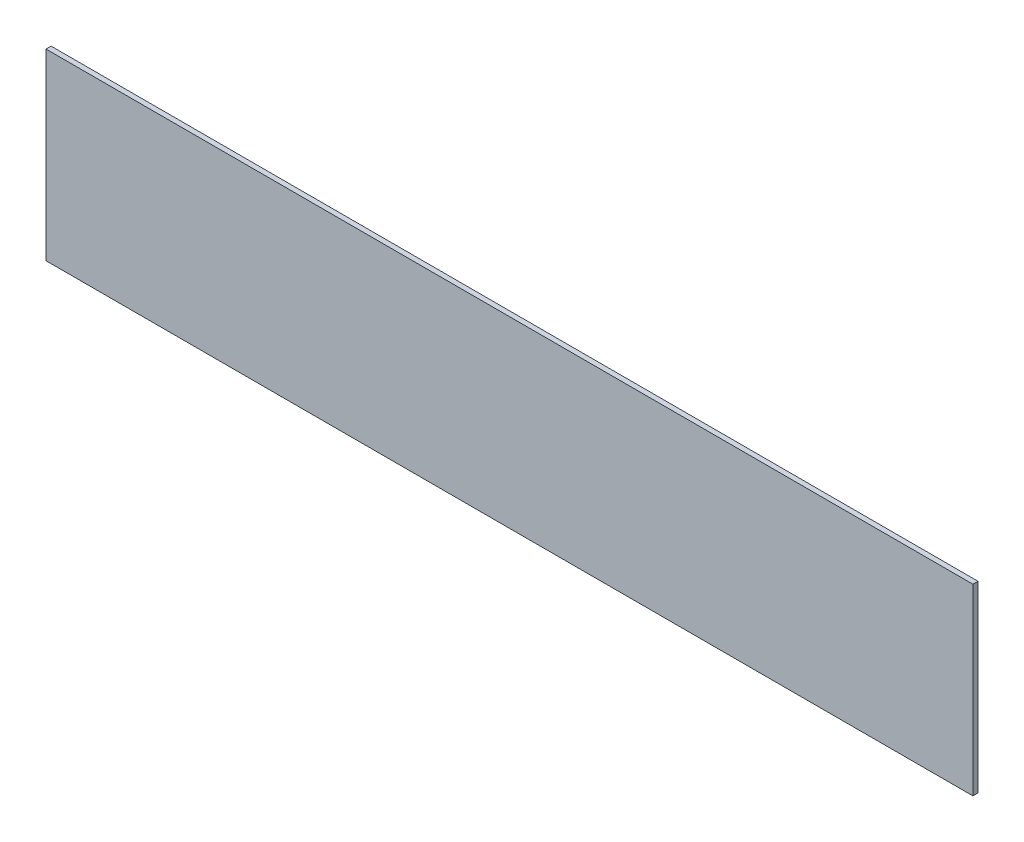
SolidWorks part; units mm, degrees
ref_plane "Front Plane" through (0, 0, 0) normal (0, 0, 1) x (1, 0, 0)
ref_plane "Top Plane" through (0, 0, 0) normal (0, 1, 0) x (1, 0, 0)
ref_plane "Right Plane" through (0, 0, 0) normal (1, 0, 0) x (0, 0, -1)
other "Configuration Table"
sketch "Sketch1" plane through (0, 0, 0) normal (0, 0, 1) x (1, 0, 0)
  line L1 (259, 312) -> (441, 312)
  line L2 (259, 312) -> (259, 348)
  line L3 (259, 348) -> (441, 348)
  line L4 (441, 312) -> (441, 348)
extrude "TOPPING_klape_alt2_kulp_cukuru_1" add sketch "Sketch1" along normal blind 1 from offset 26 separate body
